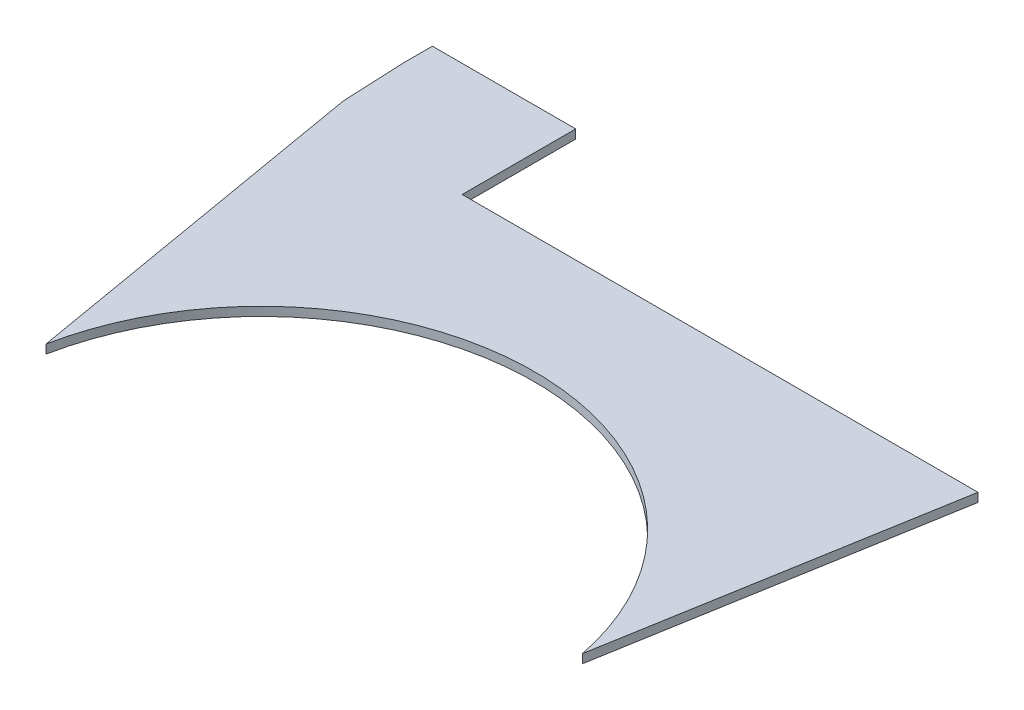
SolidWorks part; units mm, degrees
ref_plane "前视基准面" through (0, 0, 0) normal (0, 0, 1) x (1, 0, 0)
ref_plane "上视基准面" through (0, 0, 0) normal (0, 1, 0) x (1, 0, 0)
ref_plane "右视基准面" through (0, 0, 0) normal (1, 0, 0) x (0, 0, -1)
other "Configuration Table"
sketch "草图1" plane through (0, 0, 0) normal (0, 1, 0) x (1, 0, 0)
  line L0 (-13.2748, -82.8278) -> (-27.3224, -82.8278)
  line L1 (27.3224, -82.8278) -> (13.2748, -82.8278)
  line L2 (39.0308, -14.8139) -> (27.3224, -82.8278)
  line L3 (-21.5, -14.8139) -> (39.0308, -14.8139)
  line L4 (-21.5, -14.8139) -> (-21.5, -20.4375)
  line L5 (-21.5, -20.4375) -> (-38.0627, -20.4375)
  line L6 (-27.3224, -82.8278) -> (-38.0627, -20.4375)
  arc A0 (13.2748, -82.8278) -> (-13.2748, -82.8278) centre (0, -59.1141) ccw
sketch "草图2" plane through (0, 0, 0) normal (0, 1, 0) x (1, 0, 0)
  line L0 (-37.75, -5.1875) -> (-37.4278, -12.3369)
  line L28 (-30.4108, -53.0987) -> (-37.4278, -12.3369)
  line L29 (-27.3224, -82.8278) -> (-38.0627, -20.4375) construction
  line L30 (-19.5, -16.8139) -> (-19.5, 0.0625) construction
  line L31 (-19.5, 0.0625) -> (-38.75, 0.0625) construction
  line L32 (-38.0627, -20.4375) -> (-38.75, -5.1875) construction
  line L33 (-38.75, -5.1875) -> (-38.75, 0.0625) construction
  line L35 (25.6373, -80.8278) -> (13.2748, -80.8278)
  line L36 (-13.2748, -80.8278) -> (-25.6373, -80.8278)
  line L37 (-25.6373, -80.8278) -> (-35.689, -22.4375)
  line L60 (-35.689, -22.4375) -> (-19.5, -22.4375)
  line L61 (36.6571, -16.8139) -> (25.6373, -80.8278)
  line L62 (-19.5, -16.8139) -> (36.6571, -16.8139)
  line L63 (-19.5, -22.4375) -> (-19.5, -16.8139)
  line L64 (-37.75, -5.1875) -> (-37.75, -1.9375)
  line L66 (-21.5, -1.9375) -> (-37.75, -1.9375)
  line L68 (36.6571, -16.8139) -> (30.4108, -53.0987)
  line L71 (-21.5, -14.8139) -> (-21.5, -1.9375)
  line L73 (36.6571, -16.8139) -> (37.0014, -14.8139)
  line L74 (-21.5, -14.8139) -> (39.0308, -14.8139) construction
  line L75 (37.0014, -14.8139) -> (-21.5, -14.8139)
  line L76 (-21.5, -20.4375) -> (-38.0627, -20.4375) construction
  circle A0 centre (0, -59.1141) radius 30 construction
  arc A1 (30.4108, -53.0987) -> (-30.4108, -53.0987) centre (0, -59.1141) ccw
  circle A2 centre (0, -59.1141) radius 31 construction
  dimension "D2" = 60
  dimension "D1" = 2
  dimension "D4" = 20.5
  dimension "D5" = 19.25
  dimension "D6" = 5.25
  dimension "D7" = 2
  dimension "D8" = 2
  dimension "D9" = 2
  dimension "D3" = 1
extrude "凸台-拉伸1" add sketch "草图2" along normal blind 1
sketch "草图3" plane through (0, 0, 0) normal (0, 1, 0) x (1, 0, 0)
  line L0 (-35.0561, -26.1141) -> (35.0561, -26.1141) construction
  line L1 (-37.4278, -12.3369) -> (-30.4108, -53.0987) construction
  line L2 (30.4108, -53.0987) -> (37.0014, -14.8139) construction
  arc A0 (30.4108, -53.0987) -> (-30.4108, -53.0987) centre (0, -59.1141) ccw construction
  text T0 "UP" font "@Adobe 繁黑體 Std B" height 5
  dimension "D1" = 33
extrude "凸台-拉伸2" add sketch "草图3" against normal blind 1
